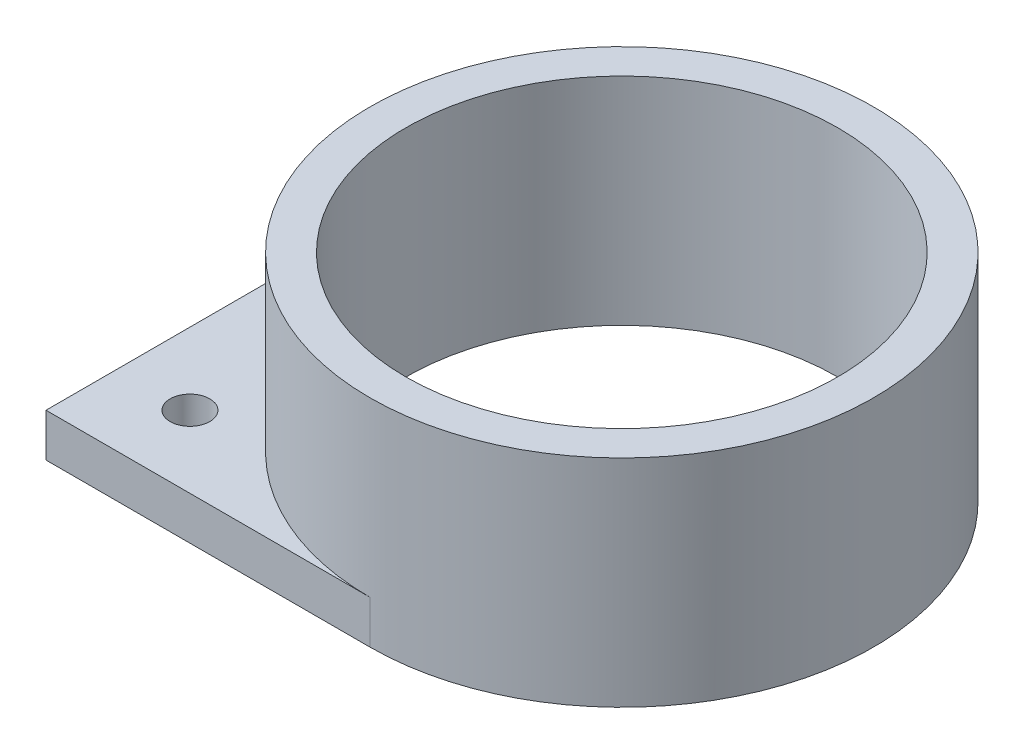
SolidWorks part; units mm, degrees
ref_plane "Front Plane" through (0, 0, 0) normal (0, 0, 1) x (1, 0, 0)
ref_plane "Top Plane" through (0, 0, 0) normal (0, 1, 0) x (1, 0, 0)
ref_plane "Right Plane" through (0, 0, 0) normal (1, 0, 0) x (0, 0, -1)
sketch "Sketch1" plane through (0, 0, 0) normal (0, 1, 0) x (1, 0, 0)
  circle A0 centre (0, 0) radius 30
  circle A1 centre (0, 0) radius 35
  dimension "D1" = 60
  dimension "D2" = 5
extrude "Boss-Extrude1" add sketch "Sketch1" along normal blind 30
sketch "Sketch2" plane through (0, 0, 0) normal (0, -1, 0) x (1, 0, 0)
  line L0 (0, -35) -> (-45, -35)
  line L1 (-45, -35) -> (-45, 35)
  line L2 (-45, 35) -> (0, 35)
  circle A0 centre (0, 0) radius 35 construction
  arc A1 (0, 35) -> (0, -35) centre (0, 0) ccw
  dimension "D1" = 45
extrude "Boss-Extrude2" add sketch "Sketch2" against normal blind 6
sketch "Sketch3" plane through (0, 6, 0) normal (0, 1, 0) x (1, 0, 0)
sketch "Sketch5" plane through (0, 6, 0) normal (0, 1, 0) x (1, 0, 0)
  line L1 (0, 0) -> (-11.2746, 0) construction
  line L3 (-45, 35) -> (0, 35) construction
  line L4 (-45, -35) -> (-45, 35) construction
  point P0 (-35, 25)
  point P16 (0, 0)
  point P17 (-35, -25)
  dimension "D1" = 10
  dimension "D2" = 10
hole_wizard "M5 Clearance Hole1" positions "Sketch5" profile "Sketch4" hole size "M5" standard "DIN"
sketch "Sketch4" plane through (-35, 6, -25) normal (1, 0, 0) x (0, 0, 1)
  line L0 (0, 0) -> (0, 11.6524)
  line L1 (0, 11.6524) -> (2.75, 10)
  line L2 (2.75, 10) -> (2.75, 0)
  line L5 (2.75, 0) -> (0, 0)
  line L10 (0, 11.6524) -> (-2.75, 10) construction
  line L11 (0, -6.35) -> (0, 107.95) construction
  dimension "Hole Dia." = 5.5
  dimension "Hole Depth" = 10
  dimension "Drill Angle" = 118
